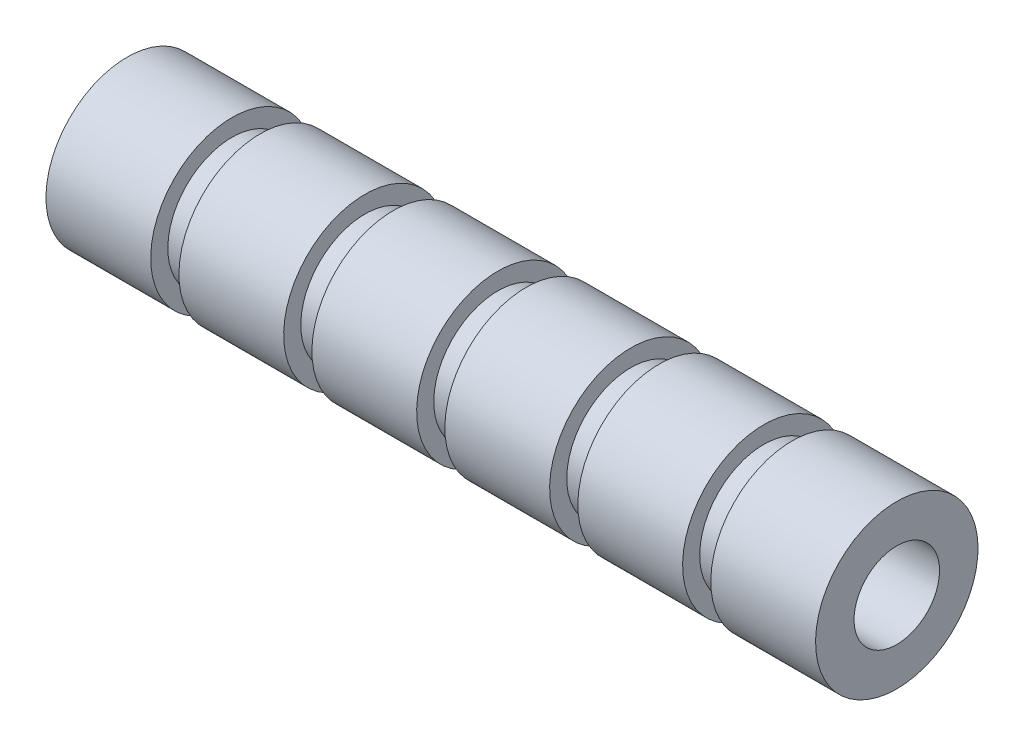
SolidWorks part; units mm, degrees
ref_plane "Front Plane" through (0, 0, 0) normal (0, 0, 1) x (1, 0, 0)
ref_plane "Top Plane" through (0, 0, 0) normal (0, 1, 0) x (1, 0, 0)
ref_plane "Right Plane" through (0, 0, 0) normal (1, 0, 0) x (0, 0, -1)
sketch "Sketch1" plane through (0, 0, 0) normal (0, 0, 1) x (1, 0, 0)
  line L0 (-45, 0) -> (45, 0)
  line L1 (55, 0) -> (-55, 0) construction
  line L2 (45, 0) -> (45, 9.5)
  line L3 (45, 9.5) -> (32.75, 9.5)
  line L4 (32.75, 9.5) -> (32.75, 7.5)
  line L5 (32.75, 7.5) -> (29.45, 7.5)
  line L6 (29.45, 7.5) -> (29.45, 9.5)
  line L7 (29.45, 9.5) -> (17.2, 9.5)
  line L8 (17.2, 9.5) -> (17.2, 7.5)
  line L9 (17.2, 7.5) -> (13.9, 7.5)
  line L10 (13.9, 7.5) -> (13.9, 9.5)
  line L11 (13.9, 9.5) -> (1.65, 9.5)
  line L12 (1.65, 9.5) -> (1.65, 7.5)
  line L13 (1.65, 7.5) -> (-1.65, 7.5)
  line L14 (-1.65, 7.5) -> (-1.65, 9.5)
  line L15 (-1.65, 9.5) -> (-13.9, 9.5)
  line L16 (-13.9, 9.5) -> (-13.9, 7.5)
  line L17 (-13.9, 7.5) -> (-17.2, 7.5)
  line L18 (-17.2, 7.5) -> (-17.2, 9.5)
  line L19 (-17.2, 9.5) -> (-29.45, 9.5)
  line L20 (-29.45, 9.5) -> (-29.45, 7.5)
  line L21 (-29.45, 7.5) -> (-32.75, 7.5)
  line L22 (-32.75, 7.5) -> (-32.75, 9.5)
  line L23 (-32.75, 9.5) -> (-45, 9.5)
  line L24 (-45, 9.5) -> (-45, 0)
  line L25 (0, -55) -> (0, 55) construction
  point P0 (0, 7.5)
  dimension "D1" = 90
  dimension "D2" = 3.3
  dimension "D3" = 7.5
  dimension "D4" = 9.5
revolve "Revolve1" add sketch "Sketch1" angle 360 about L0
sketch "Sketch2" plane through (45, 0, 0) normal (1, 0, 0) x (0, 0, -1)
  circle A0 centre (0, 0) radius 5
  dimension "D1" = 10
extrude "Cut-Extrude1" cut sketch "Sketch2" against normal through all
